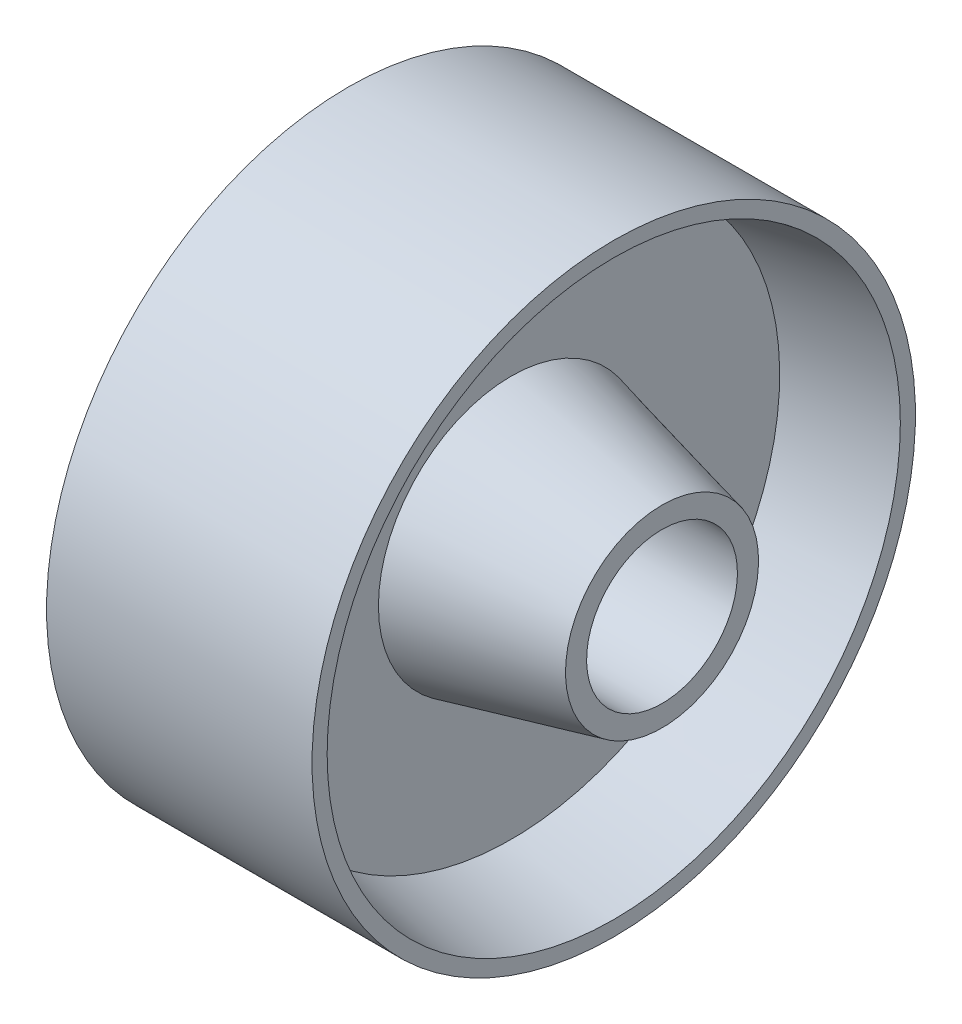
SolidWorks part; units mm, degrees
ref_plane "Alzado" through (0, 0, 0) normal (0, 0, 1) x (1, 0, 0)
ref_plane "Planta" through (0, 0, 0) normal (0, 1, 0) x (1, 0, 0)
ref_plane "Vista lateral" through (0, 0, 0) normal (1, 0, 0) x (0, 0, -1)
sketch "Croquis1" plane through (0, 0, 0) normal (0, 0, 1) x (1, 0, 0)
  line L0 (0, 0) -> (-30.6578, 0) construction
  line L1 (-5, 9.6364) -> (-5, -12.8636)
  line L2 (-5, -12.8636) -> (-30, -18.8636)
  line L3 (-30, -18.8636) -> (-30, -22.3636)
  line L4 (-30, -22.3636) -> (30, -22.3636)
  line L5 (0, 0) -> (0, 9.6364) construction
  line L6 (-5, 9.6364) -> (-22, 12.6364)
  line L7 (-22, 12.6364) -> (-22, 15.1364)
  line L8 (-22, 15.1364) -> (22, 15.1364)
  line L9 (30, -18.8636) -> (30, -22.3636)
  line L10 (5, -12.8636) -> (30, -18.8636)
  line L11 (5, 9.6364) -> (5, -12.8636)
  line L12 (5, 9.6364) -> (22, 12.6364)
  line L13 (22, 12.6364) -> (22, 15.1364)
  line L14 (0, -22.3636) -> (0, -34.8636) construction
  line L15 (0, -34.8636) -> (-47.0405, -34.8636) construction
  point P13 (0, -22.3636)
  point P18 (0, 15.1364)
  dimension "D1" = 3
  dimension "D2" = 3.5
  dimension "D3" = 6
  dimension "D4" = 22.5
  dimension "D5" = 2.5
  dimension "D6" = 22
  dimension "D7" = 30
  dimension "D8" = 5
  dimension "D9" = 8
  dimension "D10" = 17
  dimension "D11" = 12.5
revolve "Revolución1" add sketch "Croquis1" angle 360 about L15
